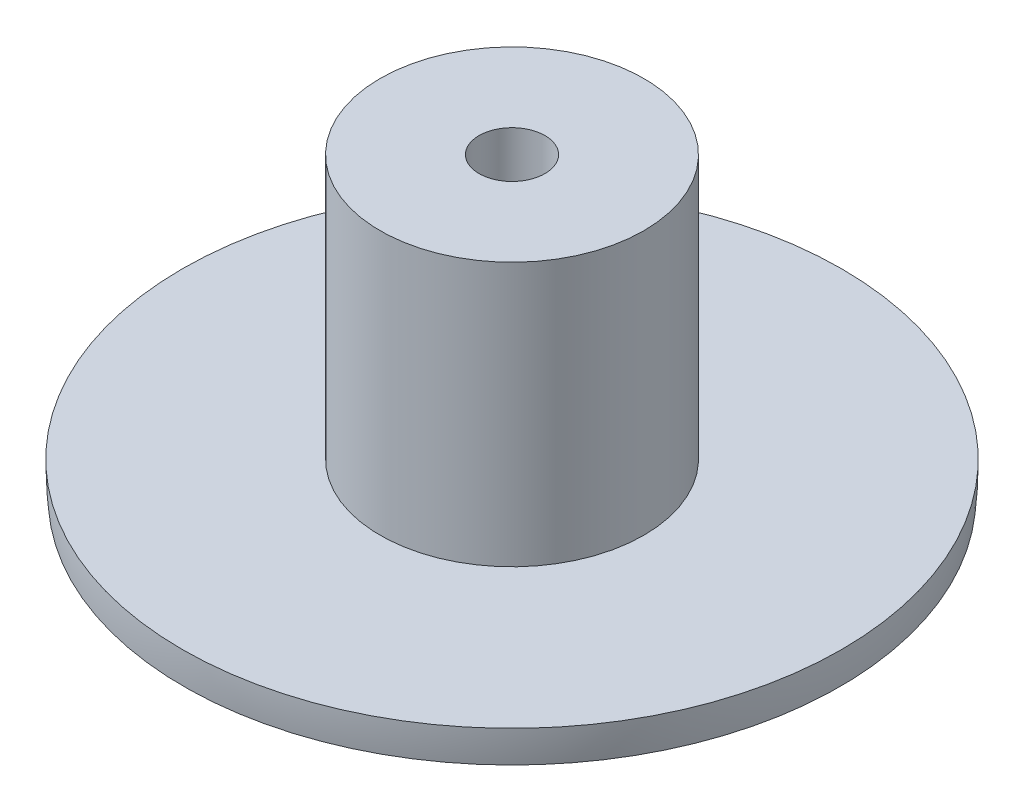
SolidWorks part; units mm, degrees
ref_plane "Front Plane" through (0, 0, 0) normal (0, 0, 1) x (1, 0, 0)
ref_plane "Top Plane" through (0, 0, 0) normal (0, 1, 0) x (1, 0, 0)
ref_plane "Right Plane" through (0, 0, 0) normal (1, 0, 0) x (0, 0, -1)
sketch "Sketch1" plane through (0, 0, 0) normal (0, 0, 1) x (1, 0, 0)
  line L0 (0, 0) -> (63.5, 0)
  line L1 (0, 0) -> (0, -6.35)
  line L2 (0, -6.35) -> (63.1817, -6.35)
  arc A0 (63.1817, -6.35) -> (63.5, 0) centre (0, 0) ccw
revolve "Revolve2" add sketch "Sketch1" angle 360 about L1
sketch "Sketch2" plane through (0, 0, 0) normal (0, 1, 0) x (1, 0, 0)
  circle A0 centre (0, 0) radius 25.4
extrude "Boss-Extrude1" add sketch "Sketch2" along normal blind 50.8
sketch "Sketch4" plane through (0, 50.8, 0) normal (0, 1, 0) x (1, 0, 0)
  circle A0 centre (0, 0) radius 6.35
extrude "Cut-Extrude1" cut sketch "Sketch4" against normal blind 87.884
